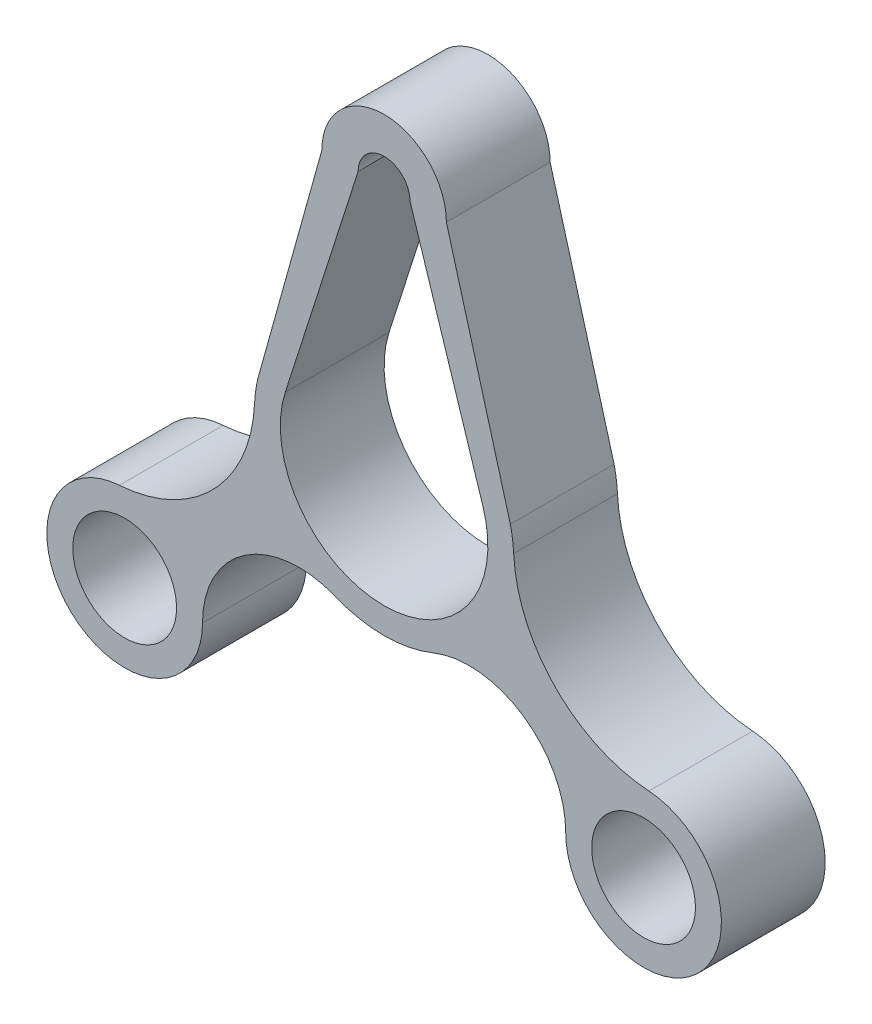
SolidWorks part; units mm, degrees
ref_plane "Front Plane" through (0, 0, 0) normal (0, 0, 1) x (1, 0, 0)
ref_plane "Top Plane" through (0, 0, 0) normal (0, 1, 0) x (1, 0, 0)
ref_plane "Right Plane" through (0, 0, 0) normal (1, 0, 0) x (0, 0, -1)
sketch "Sketch1" plane through (0, 0, 0) normal (0, 0, 1) x (1, 0, 0)
  line L0 (0, -58.8818) -> (0, 74679.5064) construction
  line L1 (1.7856, -0.375) -> (74740.1736, -3.0565) construction
  line L2 (12, 50) -> (24.3243, 5.7732)
  line L3 (5, 50) -> (19.0486, 6.0951)
  line L4 (-12, 50) -> (-24.3243, 5.7732)
  line L5 (-5, 50) -> (-19.0486, 6.0951)
  arc A0 (-19.0486, 6.0951) -> (19.0486, 6.0951) centre (0, 0) ccw
  arc A1 (-23.8045, 7.6384) -> (-24.9972, -0.374) centre (0, 0) ccw
  arc A2 (5, 50) -> (-5, 50) centre (0, 50) ccw
  arc A4 (12, 50) -> (-12, 50) centre (0, 50) ccw
  arc A5 (35, -40.3767) -> (51.0215, -25.4115) centre (50, -40.3767) ccw
  circle A6 centre (50, -40.3767) radius 10
  arc A7 (24.9719, 1.1845) -> (51.0215, -25.4115) centre (52.9274, 2.5104) ccw
  arc A8 (9.415, -23.1594) -> (35, -40.3767) centre (16.4144, -40.3767) cw
  circle A9 centre (-50, -40.3767) radius 10
  arc A10 (-35, -40.3767) -> (-51.0215, -25.4115) centre (-50, -40.3767) cw
  arc A11 (-9.415, -23.1594) -> (-35, -40.3767) centre (-16.4144, -40.3767) ccw
  arc A12 (-24.9719, 1.1845) -> (-51.0215, -25.4115) centre (-52.9274, 2.5104) cw
  arc A13 (-9.415, -23.1594) -> (9.415, -23.1594) centre (0, 0) ccw
  arc A14 (24.9972, -0.3758) -> (23.8045, 7.6384) centre (0, 0) ccw
  point P22 (50, -25.2423)
  point P27 (24.3243, -1.9889)
  point P28 (35, -40.4137)
  point P29 (35, -39.5213)
  dimension "D1" = 40
  dimension "D2" = 50
  dimension "D3" = 10
  dimension "D4" = 20
  dimension "D6" = 30
  dimension "D5" = 50
  dimension "D7" = 50
  dimension "D8" = 40
extrude "Boss-Extrude1" add sketch "Sketch1" along normal mid plane 20
